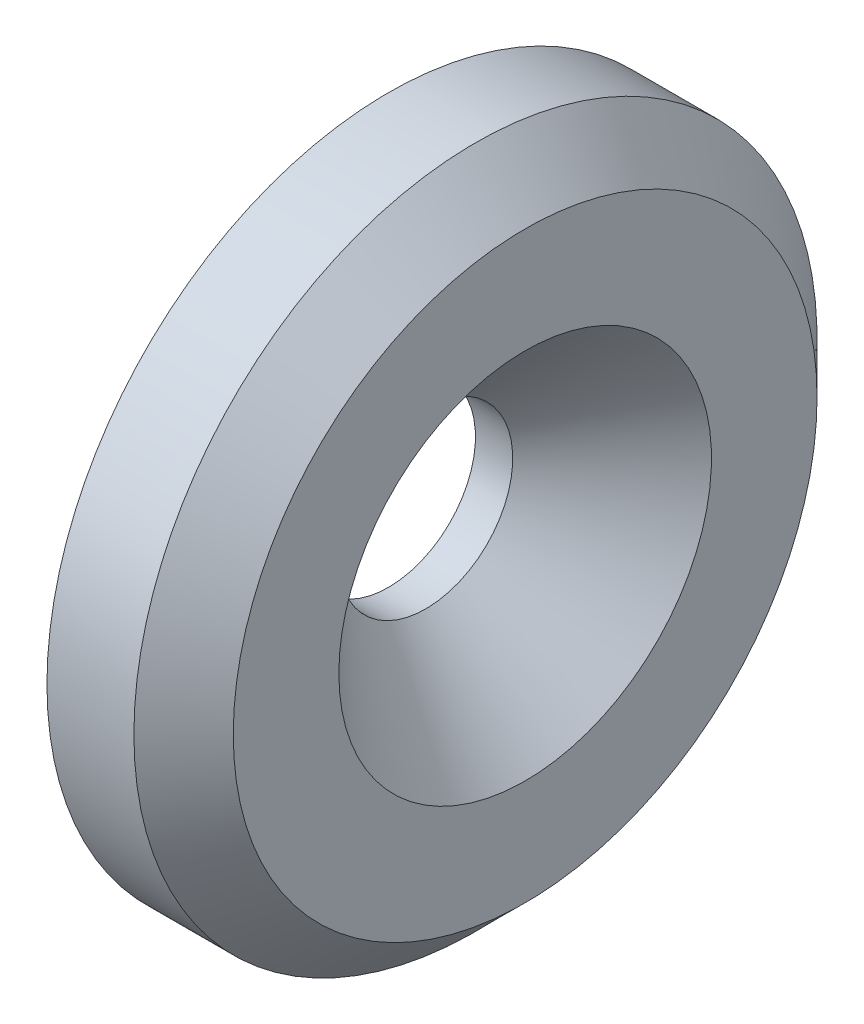
SolidWorks part; units mm, degrees
material "1.4305 (X8CrNiS18-9)"
ref_plane "Vorne" through (0, 0, 0) normal (0, 0, 1) x (1, 0, 0)
ref_plane "Oben" through (0, 0, 0) normal (0, 1, 0) x (1, 0, 0)
ref_plane "Rechts" through (0, 0, 0) normal (1, 0, 0) x (0, 0, -1)
sketch "Skizze1" plane through (0, 0, 0) normal (0, 0, 1) x (1, 0, 0)
  line L0 (-50.1147, 0) -> (15.128, 0) construction
  line L1 (-5.5, 3.5) -> (-5.5, 13.75)
  line L2 (-5.5, 13.75) -> (-2, 13.75)
  line L3 (0, 11.75) -> (0, 7.5)
  line L4 (0, 7.5) -> (-4, 3.5)
  line L5 (-4, 3.5) -> (-5.5, 3.5)
  line L6 (-2, 13.75) -> (0, 11.75)
  point P6 (0, 13.75)
  dimension "D1" = 45
  dimension "D2" = 1.5
  dimension "D3" = 5.5
  dimension "D4" = 7
  dimension "D5" = 27.5
revolve "Rotation1" add sketch "Skizze1" angle 360 about L0
